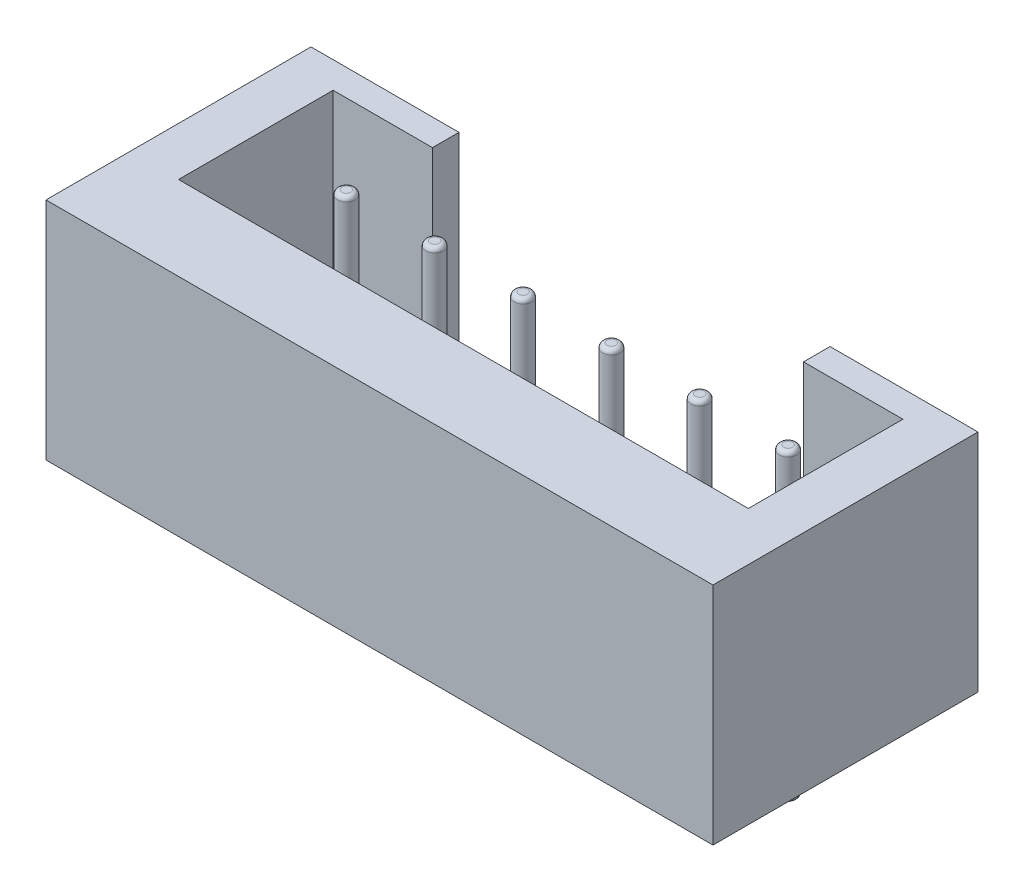
SolidWorks part; units mm, degrees
ref_plane "Front Plane" through (0, 0, 0) normal (0, 0, 1) x (1, 0, 0)
ref_plane "Top Plane" through (0, 0, 0) normal (0, 1, 0) x (1, 0, 0)
ref_plane "Right Plane" through (0, 0, 0) normal (1, 0, 0) x (0, 0, -1)
sketch "Sketch1" plane through (0, 0, 0) normal (0, 1, 0) x (1, 0, 0)
  line L0 (-4.2, 3) -> (-4.2, 2.4)
  line L1 (-7.55, 3) -> (-4.2, 3)
  line L2 (-7.55, 3) -> (-7.55, -3)
  line L3 (-7.55, -3) -> (7.55, -3)
  line L4 (7.55, 3) -> (7.55, -3)
  line L5 (-4.2, 2.4) -> (-6.45, 2.4)
  line L6 (-6.45, 2.4) -> (-6.45, -1.1)
  line L11 (-6.45, -1.1) -> (0.1202, -1.1)
  line L12 (0, -55) -> (0, 55) construction
  line L13 (4.2, 3) -> (7.55, 3)
  line L14 (6.45, -1.1) -> (-0.1202, -1.1)
  line L15 (6.45, 2.4) -> (6.45, -1.1)
  line L16 (4.2, 2.4) -> (6.45, 2.4)
  line L17 (4.2, 3) -> (4.2, 2.4)
  point P0 (0, 0)
  point P6 (0, 4.7628)
  dimension "D1" = 8.4
  dimension "D2" = 15.1
  dimension "D3" = 6
  dimension "D4" = 0.6
  dimension "D5" = 1.1
  dimension "D6" = 1.9
sketch "Sketch2" plane through (0, 0, 0) normal (0, 1, 0) x (1, 0, 0)
  line L0 (4.2, 3) -> (7.55, 3) construction
  line L1 (7.55, 3) -> (7.55, -3) construction
  line L2 (-7.55, -3) -> (7.55, -3) construction
  line L3 (-7.55, 3) -> (-7.55, -3) construction
  line L4 (-7.55, 3) -> (-4.2, 3) construction
  line L5 (4.2, 3) -> (7.55, 3)
  line L6 (7.55, 3) -> (7.55, -3)
  line L7 (-7.55, -3) -> (7.55, -3)
  line L8 (-7.55, 3) -> (-7.55, -3)
  line L9 (-7.55, 3) -> (-4.2, 3)
  line L10 (-4.2, 3) -> (4.2, 3)
extrude "Boss-Extrude1" add sketch "Sketch2" along normal blind 0.6
extrude "Boss-Extrude2" add sketch "Sketch1" along normal blind 4.5 from surface at 0.6 contours L13 L17 L16 L15 L14 L11 L6 L5 L0 L1 L2 L3 L4 starting at face at (0, 0.6, 0)
sketch "Sketch3" plane through (0, 0.6, 0) normal (0, 1, 0) x (1, 0, 0)
  line L0 (-7.55, 3) -> (-4.2, 3) construction
  line L1 (-7.55, 3) -> (-7.55, -3) construction
  circle A0 centre (-4.95, 1.2) radius 0.2
  circle A1 centre (-2.95, 1.2) radius 0.2
  circle A2 centre (-0.95, 1.2) radius 0.2
  circle A3 centre (1.05, 1.2) radius 0.2
  circle A4 centre (3.05, 1.2) radius 0.2
  circle A5 centre (5.05, 1.2) radius 0.2
  dimension "D1" = 0.4
  dimension "D2" = 2.6
  dimension "D3" = 1.8
  dimension "D4" = 6
extrude "Boss-Extrude3" add sketch "Sketch3" along normal blind 3.9 and the other way blind 3
fillet "Fillet1" radius 0.1 12 edges at (-4.95, 4.5, -1) (-2.95, 4.5, -1) (-0.95, 4.5, -1) (1.05, 4.5, -1) (3.05, 4.5, -1) (5.05, 4.5, -1) (-4.95, -2.4, -1) (-2.95, -2.4, -1) (-0.95, -2.4, -1) (1.05, -2.4, -1) (3.05, -2.4, -1) (5.05, -2.4, -1)
